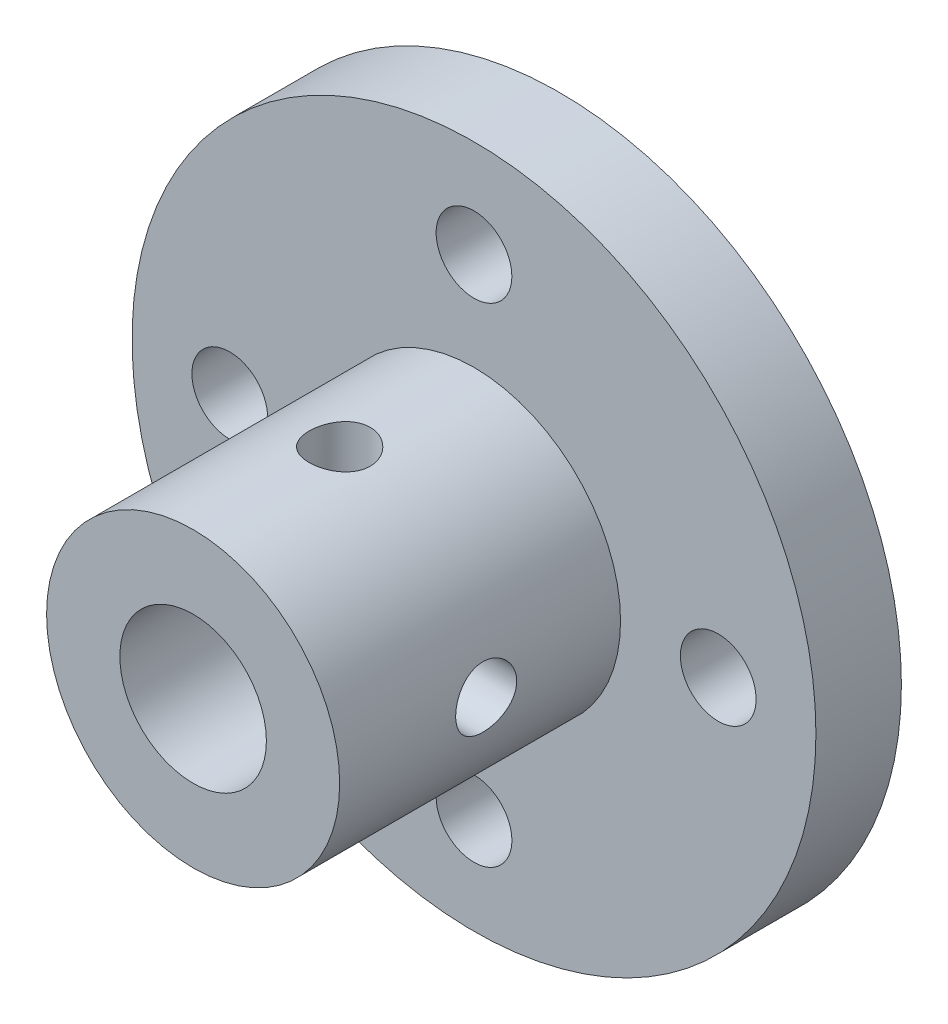
SolidWorks part; units mm, degrees
ref_plane "前视基准面" through (0, 0, 0) normal (0, 0, 1) x (1, 0, 0)
ref_plane "上视基准面" through (0, 0, 0) normal (0, 1, 0) x (1, 0, 0)
ref_plane "右视基准面" through (0, 0, 0) normal (1, 0, 0) x (0, 0, -1)
other "Configuration Table"
sketch "草图1" plane through (0, 0, 0) normal (0, 0, 1) x (1, 0, 0)
  circle A0 centre (0, 0) radius 14
  dimension "D1" = 28
extrude "凸台-拉伸1" add sketch "草图1" along normal blind 3.5
sketch "草图2" plane through (0, 0, 3.5) normal (0, 0, 1) x (1, 0, 0)
  circle A0 centre (0, 0) radius 6
  dimension "D1" = 12
extrude "凸台-拉伸2" add sketch "草图2" along normal blind 11.5
sketch "草图3" plane through (0, 0, 15) normal (0, 0, 1) x (1, 0, 0)
  circle A0 centre (0, 0) radius 3
  dimension "D1" = 6
extrude "切除-拉伸1" cut sketch "草图3" against normal through all
sketch "草图4" plane through (0, 0, 3.5) normal (0, 0, 1) x (1, 0, 0)
  circle A0 centre (0, 10) radius 1.55
  dimension "D1" = 3.1
  dimension "D2" = 10
extrude "切除-拉伸2" cut sketch "草图4" against normal through all
pattern_circular "阵列(圆周)1" count 4 over 360 about axis through (0, 0, 0) along (0, 0, 1) of "切除-拉伸2"
hole_wizard "M3 螺纹孔1" positions "草图5" profile "草图6" tap size "M3" standard "IS"
sketch "草图5" plane through (0, 0, 0) normal (1, 0, 0) x (0, 0, -1)
  line L0 (-15, 6) -> (-15, -6) construction
  line L1 (0, 0) -> (-5.2021, 0) construction
  point P0 (-9, 0)
  dimension "D1" = 6
sketch "草图6" plane through (0, 0, 9) normal (0, 1, 0) x (0, 0, 1)
  line L0 (0, 0) -> (0, 8.2511)
  line L1 (0, 8.2511) -> (1.25, 7.5)
  line L2 (1.25, 7.5) -> (1.25, 0.275)
  line L3 (1.25, 0.275) -> (1.525, 0)
  line L5 (1.525, 0) -> (0, 0)
  line L6 (-1.25, 0.275) -> (-1.525, 0) construction
  line L10 (0, 8.2511) -> (-1.25, 7.5) construction
  line L11 (0, -6.35) -> (0, 107.95) construction
  dimension "螺纹孔钻头直径" = 2.5
  dimension "螺纹孔钻头深度" = 7.5
  dimension "近端锥形沉头孔直径" = 3.05
  dimension "近端锥形沉头孔角度" = 90
  dimension "导头角度" = 118
cosmetic thread "孔螺蚊线1" parameters "D1"=6, "D2"=3
pattern_circular "阵列(圆周)2" count 2 over 90 about axis through (0, 0, 15) along (0, 0, 1) of "M3 螺纹孔1"
